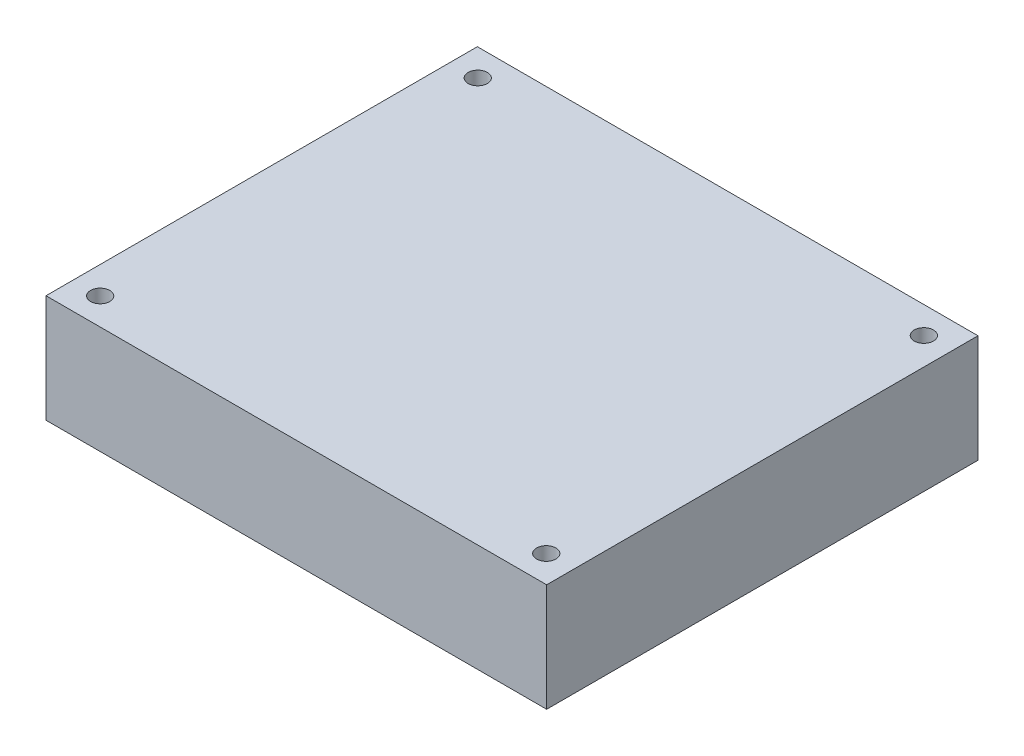
SolidWorks part; units mm, degrees
ref_plane "Front Plane" through (0, 0, 0) normal (0, 0, 1) x (1, 0, 0)
ref_plane "Top Plane" through (0, 0, 0) normal (0, 1, 0) x (1, 0, 0)
ref_plane "Right Plane" through (0, 0, 0) normal (1, 0, 0) x (0, 0, -1)
sketch "Sketch1" plane through (0, 0, 0) normal (0, 1, 0) x (1, 0, 0)
  line L1 (-32.5, -28) -> (32.5, -28)
  line L2 (-32.5, -28) -> (-32.5, 28)
  line L3 (-32.5, 28) -> (32.5, 28)
  line L4 (32.5, -28) -> (32.5, 28)
  line L5 (-32.5, -28) -> (32.5, 28) construction
  line L6 (-32.5, 28) -> (32.5, -28) construction
  point P0 (0, 0)
  dimension "D1" = 65
  dimension "D2" = 56
extrude "Boss-Extrude1" add sketch "Sketch1" along normal blind 14
sketch "Sketch2" plane through (0, 0, 0) normal (0, -1, 0) x (1, 0, 0)
  line L1 (-28.956, -24.511) -> (28.956, -24.511) construction
  line L2 (-28.956, -24.511) -> (-28.956, 24.511) construction
  line L3 (-28.956, 24.511) -> (28.956, 24.511) construction
  line L4 (28.956, -24.511) -> (28.956, 24.511) construction
  line L5 (-28.956, -24.511) -> (28.956, 24.511) construction
  line L6 (-28.956, 24.511) -> (28.956, -24.511) construction
  circle A0 centre (28.956, 24.511) radius 1.25
  circle A1 centre (28.956, -24.511) radius 1.25
  circle A2 centre (-28.956, -24.511) radius 1.25
  circle A3 centre (-28.956, 24.511) radius 1.25
  point P0 (0, 0)
  dimension "D3" = 2.5
  dimension "D1" = 57.912
  dimension "D2" = 49.022
extrude "Cut-Extrude1" cut sketch "Sketch2" against normal up to surface (14 mm away) contours A1 | A0 | A3 | A2 up to face at (0, 14, 0)
